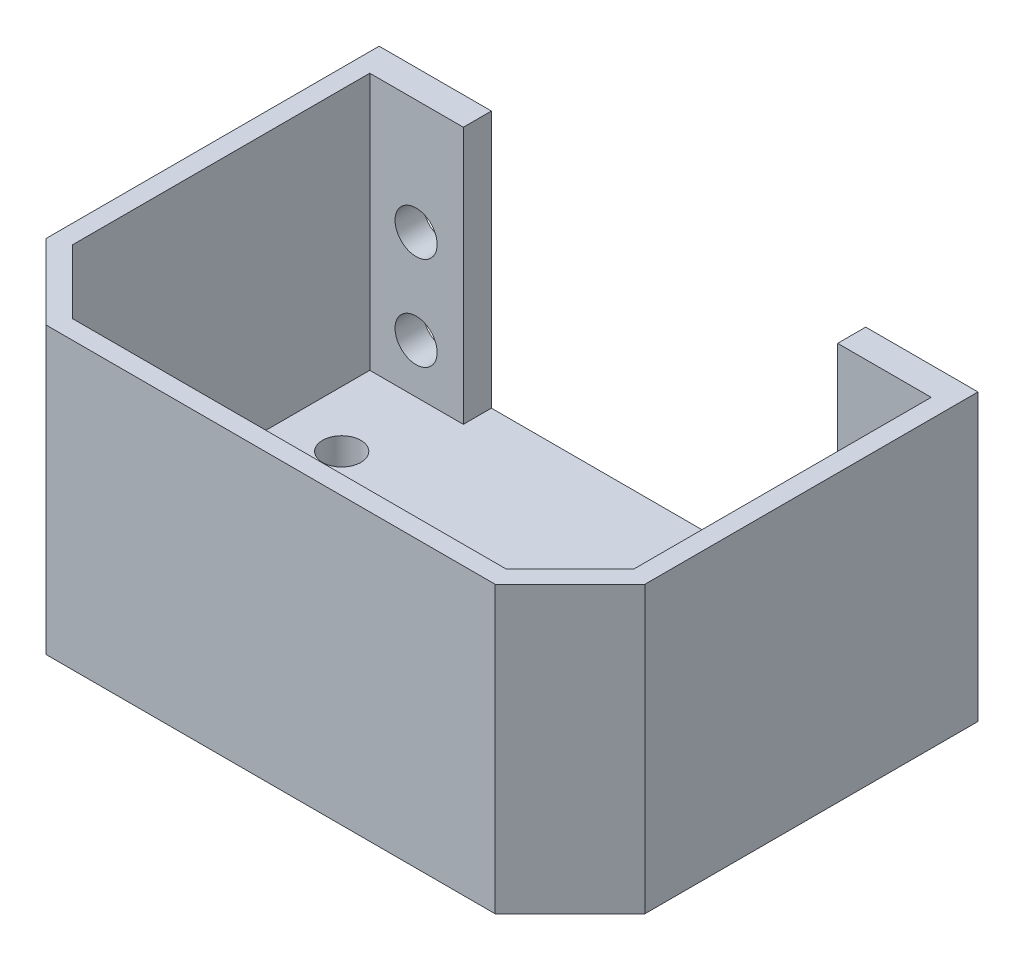
SolidWorks part; units mm, degrees
ref_plane "Front Plane" through (0, 0, 0) normal (0, 0, 1) x (1, 0, 0)
ref_plane "Top Plane" through (0, 0, 0) normal (0, 1, 0) x (1, 0, 0)
ref_plane "Right Plane" through (0, 0, 0) normal (1, 0, 0) x (0, 0, -1)
sketch "Sketch1" plane through (0, 0, 0) normal (0, 0, 1) x (1, 0, 0)
  line L0 (-32, 10.25) -> (-20, 10.25)
  line L5 (32, 10.25) -> (32, -10.25)
  line L6 (32, -10.25) -> (20, -10.25)
  line L7 (-32, -10.25) -> (-32, 10.25)
  line L11 (20, -10.25) -> (-20, -10.25) construction
  line L12 (-20, -10.25) -> (-32, -10.25)
  line L15 (-20, 10.25) -> (-20, -10.25)
  line L16 (20, 10.25) -> (32, 10.25)
  line L17 (20, 10.25) -> (20, -10.25)
  point P6 (-32, 0)
  dimension "D1" = 64
  dimension "D2" = 12
  dimension "D3" = 12
  dimension "D4" = 20.5
  dimension "D5" = 32
  dimension "D6" = 20.5
extrude "Arm Mounts" add sketch "Sketch1" along normal blind 3 contours L16 L17 L6 L5 | L15 L0 L7 L12
sketch "Sketch2" plane through (0, 0, 3) normal (0, 0, -1) x (-1, 0, 0)
  line L0 (0, 55) -> (0, -55) construction
  circle A0 centre (-25.05, 5) radius 2.25
  circle A1 centre (-25.05, -5) radius 2.25
  circle A2 centre (25.05, -5) radius 2.25
  circle A3 centre (25.05, 5) radius 2.25
  point P4 (0, 0)
  point P6 (-24.0589, -5)
  dimension "D1" = 4.5
  dimension "D2" = 4.5
  dimension "D3" = 10
  dimension "D4" = 5
  dimension "D5" = 25.05
extrude "Arm Holes" cut sketch "Sketch2" against normal blind 3 and the other way through all contours A3 | A2 | A1 | A0
sketch "Sketch3" plane through (0, 0, 0) normal (0, 0, -1) x (-1, 0, 0)
  line L1 (-32, -10.25) -> (32, -10.25)
  line L2 (-32, -10.25) -> (-32, -13.25)
  line L3 (-32, -13.25) -> (32, -13.25)
  line L4 (32, -10.25) -> (32, -13.25)
  line L5 (-32, 10.25) -> (-32, -10.25) construction
  line L6 (32, -10.25) -> (32, 10.25) construction
  line L7 (-32, -10.25) -> (-20, -10.25) construction
  dimension "D1" = 3
extrude "Bottom Plate" add sketch "Sketch3" against normal blind 28
sketch "Sketch4" plane through (-32, 0, 0) normal (-1, 0, 0) x (0, 0, 1)
  line L0 (3, 10.25) -> (28, -10.25)
  line L1 (28, -10.25) -> (3, -10.25)
  line L2 (3, -10.25) -> (3, 10.25)
extrude "Side Ribs" add sketch "Sketch4" against normal blind 2
mirror "Rib Mirror" about plane through (0, 0, 0) normal (1, 0, 0) of "Side Ribs"
sketch "Sketch5" plane through (0, -10.25, 0) normal (0, 1, 0) x (1, 0, 0)
  line L0 (-30, -28) -> (30, -28) construction
  line L1 (28, -28) -> (-8, -28)
  line L2 (28, -28) -> (28, -16)
  line L3 (28, -16) -> (-8, -16)
  line L4 (-8, -28) -> (-8, -16)
  line L5 (32, -28) -> (32, -3) construction
  dimension "D1" = 4
  dimension "D2" = 36
  dimension "D3" = 12
extrude "Cut-Extrude2" cut sketch "Sketch5" against normal blind 10
sketch "Sketch6" plane through (0, -10.25, 0) normal (0, 1, 0) x (1, 0, 0)
  line L0 (-20, 0) -> (20, 0) construction
  circle A0 centre (-24, -12) radius 2.05
  circle A1 centre (24, -10) radius 2.05
  dimension "D5" = 4.1
  dimension "D6" = 4.1
  dimension "D1" = 10
  dimension "D2" = 24
  dimension "D3" = 24
  dimension "D4" = 12
extrude "Mounting Holes" cut sketch "Sketch6" against normal blind 10
sketch "Sketch7" plane through (0, -10.25, 0) normal (0, 1, 0) x (1, 0, 0)
  line L0 (-1002.3277, -21.8) -> (48997.6723, -21.8) construction
  line L1 (-20, 0) -> (20, 0) construction
  dimension "D1" = 21.8
sketch "Sketch8" plane through (0, -10.25, 0) normal (0, 1, 0) x (1, 0, 0)
  line L0 (-201002.3277, -21.8) -> (248997.6723, -21.8) construction
  line L1 (-32, -28) -> (32, -28)
  line L2 (-32, -28) -> (-32, -21.8)
  line L3 (-32, -21.8) -> (32, -21.8)
  line L4 (32, -28) -> (32, -21.8)
  line L5 (32, -28) -> (32, -3) construction
extrude "Cut-Extrude4" cut sketch "Sketch8" against normal through all both and the other way through all
ref_plane "Plane3" through (0, 0, 21.8) normal (0, 0, 1) x (1, 0, 0)
sketch "Sketch10" plane through (0, -10.25, 0) normal (0, 1, 0) x (1, 0, 0)
  line L0 (32, -21.8) -> (32, -3) construction
  line L1 (-32, -21.8) -> (32, -21.8)
  line L2 (-32, -21.8) -> (-32, -43.6)
  line L3 (-32, -43.6) -> (32, -43.6)
  line L4 (32, -21.8) -> (32, -43.6)
  dimension "D1" = 21.8
extrude "Boss-Extrude7" add sketch "Sketch10" against normal up to surface (3 mm away) up to face at (5, -13.25, 14.9)
mirror "Mirror5" about plane through (0, 0, 21.8) normal (0, 0, 1) of "Cut-Extrude2", "Mounting Holes"
chamfer "Chamfer3" distance 5 angle 45 2 edges at (31, -10.25, 21.8) (-31, -10.25, 21.8)
chamfer "Chamfer4" distance 2.5 angle 45 4 edges at (28, -11.75, 27.6) (-8, -11.75, 27.6) (-8, -11.75, 15.6) (28, -11.75, 15.6)
chamfer "Chamfer5" distance 8 angle 45 2 edges at (-32, -11.75, 43.6) (32, -11.75, 43.6)
sketch "Sketch11" plane through (0, -10.25, 0) normal (0, 1, 0) x (1, 0, 0)
  line L3 (-8, -25.1) -> (-8, -26.5142)
  line L4 (-8, -26.5142) -> (-8.7071, -25.8071) construction
  line L5 (28, -25.1) -> (28, -26.5142)
  line L6 (28.7071, -25.8071) -> (25.9142, -28.6)
  line L7 (25.9142, -28.6) -> (-5.9142, -28.6)
  line L8 (-5.9142, -28.6) -> (-8.7071, -25.8071)
  line L9 (28, -26.5142) -> (25.9142, -28.6)
  line L10 (25.9142, -28.6) -> (-5.9142, -28.6)
  line L11 (-5.9142, -28.6) -> (-8, -26.5142)
  line L12 (28.7071, -25.8071) -> (28, -26.5142) construction
  line L13 (-8, -25.1) -> (28, -25.1)
  dimension "D1" = 1
extrude "Cut-Extrude5" cut sketch "Sketch11" against normal blind 10
sketch "Sketch12" plane through (0, -10.25, 0) normal (0, 1, 0) x (1, 0, 0)
  line L0 (-32, -26.8) -> (-32, -3)
  line L1 (-32, -3) -> (-30, -3)
  line L2 (-30, -26.8) -> (-30, -34.7716)
  line L3 (-30, -34.7716) -> (-23.1716, -41.6)
  line L4 (-23.1716, -41.6) -> (23.1716, -41.6)
  line L5 (23.1716, -41.6) -> (30, -34.7716)
  line L6 (30, -34.7716) -> (30, -26.8)
  line L7 (-30, -3) -> (-30, -26.8)
  line L8 (30, -26.8) -> (30, -3)
  line L9 (30, -3) -> (32, -3)
  line L10 (32, -3) -> (32, -26.8)
  line L14 (-32, -26.8) -> (-32, -35.6)
  line L15 (-32, -35.6) -> (-24, -43.6)
  line L16 (-24, -43.6) -> (24, -43.6)
  line L17 (24, -43.6) -> (32, -35.6)
  line L18 (32, -35.6) -> (32, -26.8)
  line L19 (32, -26.8) -> (30, -26.8)
  line L20 (30, -26.8) -> (30, -3)
  line L21 (30, -3) -> (20, -3)
  line L22 (20, -3) -> (20, 0)
  line L23 (20, 0) -> (-20, 0)
  line L24 (-20, 0) -> (-20, -3)
  line L25 (-20, -3) -> (-30, -3)
  line L26 (-30, -3) -> (-30, -26.8)
  line L27 (-30, -26.8) -> (-32, -26.8)
  line L28 (-32, -26.8) -> (-32, -35.6)
  line L29 (-32, -35.6) -> (-24, -43.6)
  line L30 (-24, -43.6) -> (24, -43.6)
  line L31 (24, -43.6) -> (32, -35.6)
  line L32 (32, -35.6) -> (32, -26.8)
  dimension "D1" = 0
  dimension "D2" = 2
extrude "Boss-Extrude8" add sketch "Sketch12" along normal up to surface (20.5 mm away) up to face at (-26.8, 10.25, 1.8)
sketch "Sketch13" plane through (0, 10.25, 0) normal (0, 1, 0) x (1, 0, 0)
  line L16 (-20, 0) -> (-32, 0)
  line L17 (-32, 0) -> (-32, -35.6)
  line L18 (-32, -35.6) -> (-24, -43.6)
  line L19 (-24, -43.6) -> (24, -43.6)
  line L20 (24, -43.6) -> (32, -35.6)
  line L21 (32, -35.6) -> (32, 0)
  line L22 (32, 0) -> (20, 0)
  line L23 (20, 0) -> (20, -3)
  line L24 (20, -3) -> (30, -3)
  line L25 (30, -3) -> (30, -34.7716)
  line L26 (30, -34.7716) -> (23.1716, -41.6)
  line L27 (23.1716, -41.6) -> (-23.1716, -41.6)
  line L28 (-23.1716, -41.6) -> (-30, -34.7716)
  line L29 (-30, -34.7716) -> (-30, -3)
  line L30 (-30, -3) -> (-20, -3)
  line L31 (-20, -3) -> (-20, 0)
  line L32 (-20, 0) -> (-32, 0)
  line L33 (-32, 0) -> (-32, -35.6)
  line L34 (-32, -35.6) -> (-24, -43.6)
  line L35 (-24, -43.6) -> (24, -43.6)
  line L36 (24, -43.6) -> (32, -35.6)
  line L37 (32, -35.6) -> (32, 0)
  line L38 (32, 0) -> (20, 0)
  line L39 (20, 0) -> (20, -3)
  line L40 (20, -3) -> (30, -3)
  line L41 (30, -3) -> (30, -34.7716)
  line L42 (30, -34.7716) -> (23.1716, -41.6)
  line L43 (23.1716, -41.6) -> (-23.1716, -41.6)
  line L44 (-23.1716, -41.6) -> (-30, -34.7716)
  line L45 (-30, -34.7716) -> (-30, -3)
  line L46 (-30, -3) -> (-20, -3)
  line L47 (-20, -3) -> (-20, 0)
  dimension "D1" = 0
extrude "Boss-Extrude9" add sketch "Sketch13" along normal blind 7
